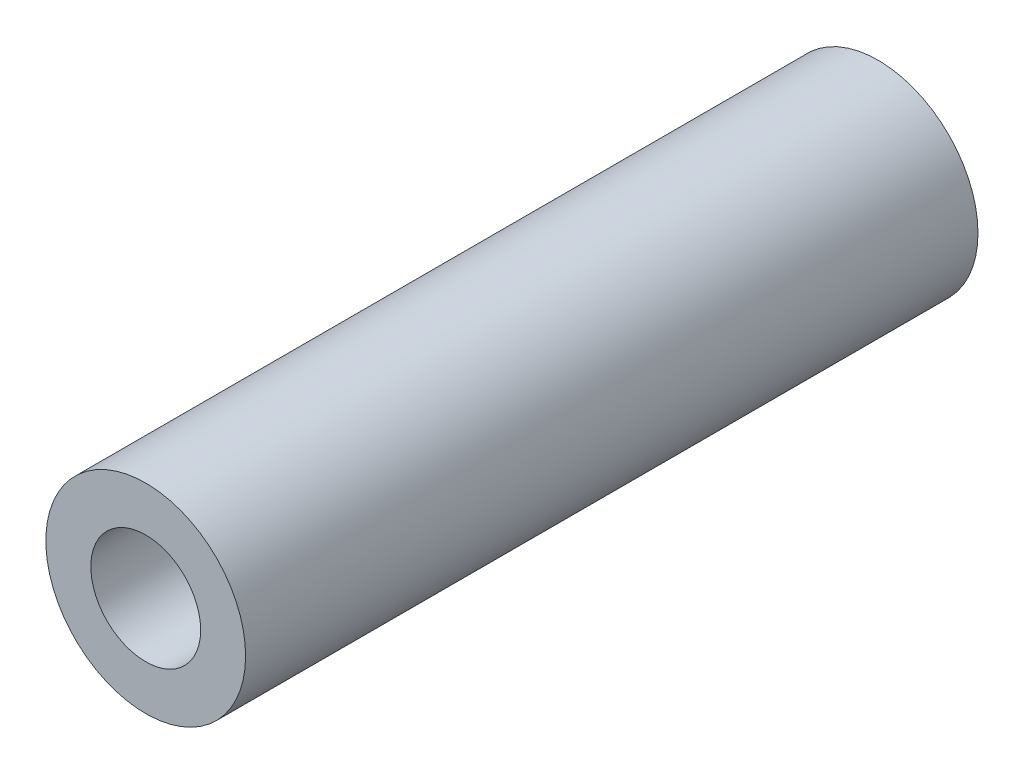
SolidWorks part; units mm, degrees
ref_plane "Ebene vorne" through (0, 0, 0) normal (0, 0, 1) x (1, 0, 0)
ref_plane "Ebene oben" through (0, 0, 0) normal (0, 1, 0) x (1, 0, 0)
ref_plane "Ebene rechts" through (0, 0, 0) normal (1, 0, 0) x (0, 0, -1)
sketch "Skizze1" plane through (0, 0, 0) normal (0, 0, 1) x (1, 0, 0)
  circle A0 centre (0, 0) radius 1.65
  circle A1 centre (0, 0) radius 3
  dimension "D1" = 3.3
  dimension "D2" = 6
extrude "Aufsatz-Linear austragen1" add sketch "Skizze1" along normal blind 22
